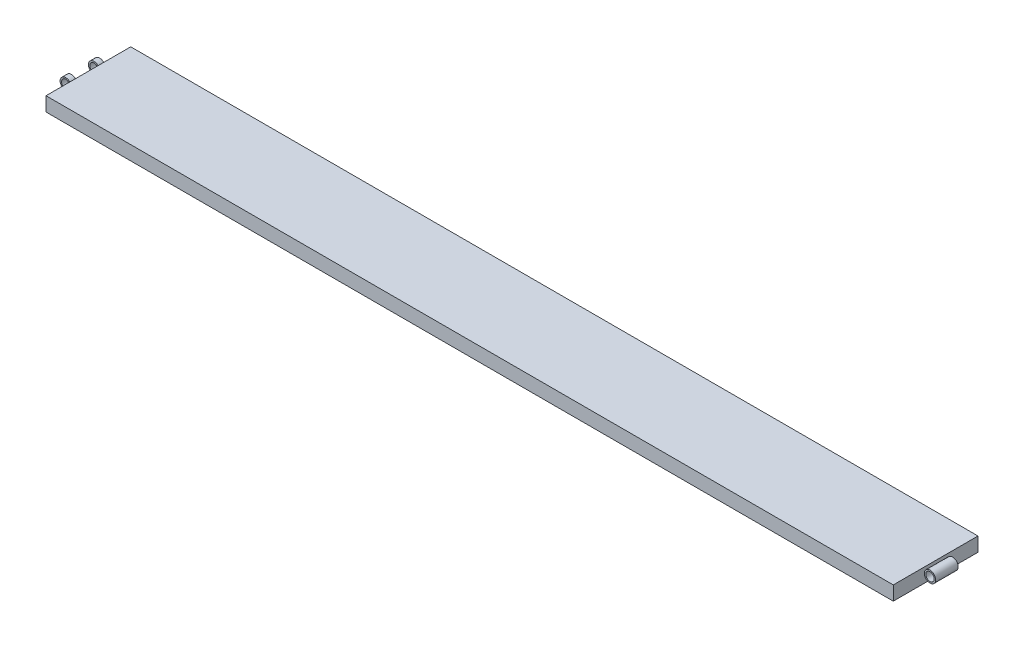
SolidWorks part; units mm, degrees
ref_plane "Front Plane" through (0, 0, 0) normal (0, 0, 1) x (1, 0, 0)
ref_plane "Top Plane" through (0, 0, 0) normal (0, 1, 0) x (1, 0, 0)
ref_plane "Right Plane" through (0, 0, 0) normal (1, 0, 0) x (0, 0, -1)
sketch "Sketch1" plane through (0, 0, 0) normal (0, 1, 0) x (1, 0, 0)
  line L1 (0, 0) -> (381, 0)
  line L2 (0, 0) -> (0, 38.1)
  line L3 (0, 38.1) -> (381, 38.1)
  line L4 (381, 0) -> (381, 38.1)
  dimension "D1" = 381
  dimension "D2" = 38.1
extrude "Boss-Extrude1" add sketch "Sketch1" along normal blind 6.35
ref_plane "Plane1" through (0, 0, -12.7) normal (0, 0, 1) x (1, 0, 0)
sketch "Sketch2" plane through (0, 0, -12.7) normal (0, 0, 1) x (1, 0, 0)
  line L0 (0, 6.35) -> (0, 0) construction
  circle A0 centre (-2.54, 3.8728) radius 2.54
  circle A1 centre (-2.54, 3.8728) radius 1.905
  dimension "D1" = 5.08
  dimension "D3" = 3.81
  dimension "D2" = 3.8728
extrude "Boss-Extrude2" add sketch "Sketch2" along normal blind 1.27 and the other way blind 1.27 separate body
ref_plane "Plane2" through (0, 0, -19.05) normal (0, 0, 1) x (1, 0, 0)
pattern_linear "LPattern1" count 2 spacing 12.7 along (0, 0, -1) of "Boss-Extrude2"
sketch "Sketch4" plane through (0, 0, -19.05) normal (0, 0, 1) x (1, 0, 0)
  circle A5 centre (383.54, 3.8728) radius 1.905
  circle A6 centre (383.54, 3.8728) radius 2.54
  dimension "D3" = 3.81
  dimension "D4" = 5.08
  dimension "D1" = 383.54
  dimension "D2" = 3.8728
extrude "Boss-Extrude4" add sketch "Sketch4" along normal blind 5.08 and the other way blind 5.08 separate body
